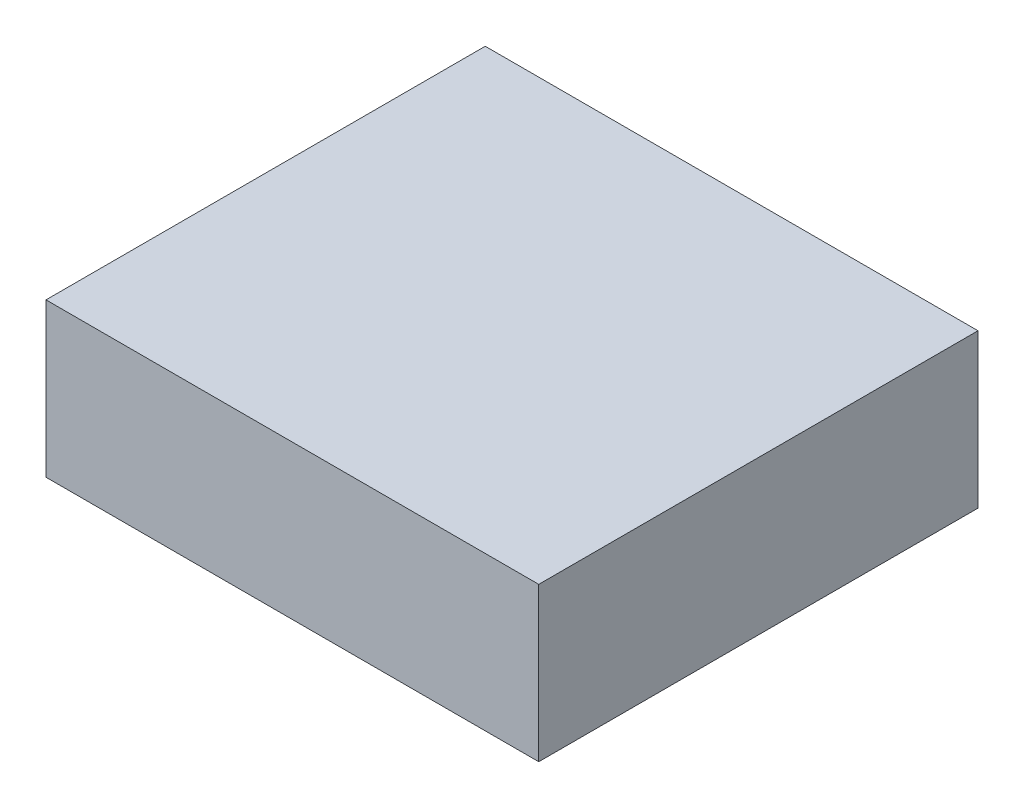
SolidWorks part; units mm, degrees
ref_plane "Front Plane" through (0, 0, 0) normal (0, 0, 1) x (1, 0, 0)
ref_plane "Top Plane" through (0, 0, 0) normal (0, 1, 0) x (1, 0, 0)
ref_plane "Right Plane" through (0, 0, 0) normal (1, 0, 0) x (0, 0, -1)
other "Configuration Table"
sketch "Sketch1" plane through (0, 0, 0) normal (0, 1, 0) x (1, 0, 0)
  line L1 (-62.4779, 63.937) -> (64.6003, 63.937)
  line L2 (-62.4779, 63.937) -> (-62.4779, -49.3456)
  line L3 (-62.4779, -49.3456) -> (64.6003, -49.3456)
  line L4 (64.6003, 63.937) -> (64.6003, -49.3456)
extrude "Boss-Extrude1" add sketch "Sketch1" along normal blind 39.624
